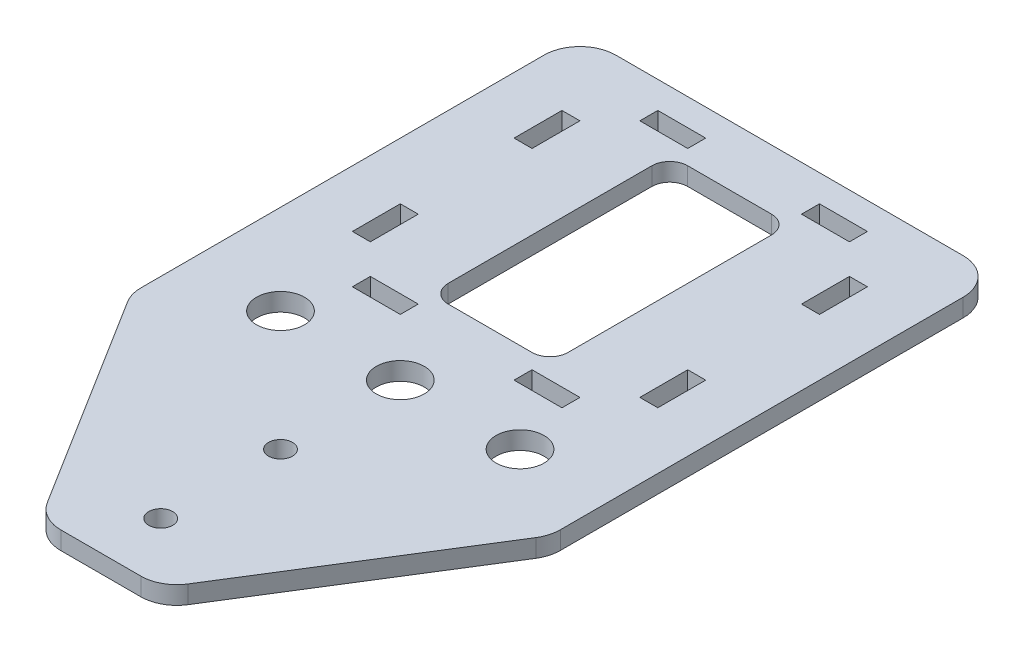
SolidWorks part; units mm, degrees
ref_plane "前视基准面" through (0, 0, 0) normal (0, 0, 1) x (1, 0, 0)
ref_plane "上视基准面" through (0, 0, 0) normal (0, 1, 0) x (1, 0, 0)
ref_plane "右视基准面" through (0, 0, 0) normal (1, 0, 0) x (0, 0, -1)
other "Configuration Table"
sketch "草图1" plane through (0, 0, 0) normal (0, 1, 0) x (1, 0, 0)
  line L0 (-35, -45) -> (-10, -85)
  line L1 (-35, 45) -> (35, 45)
  line L2 (-35, 45) -> (-35, -45)
  line L3 (-35, -45) -> (35, -45)
  line L4 (35, 45) -> (35, -45)
  line L5 (-35, 45) -> (35, -45) construction
  line L6 (-35, -45) -> (35, 45) construction
  line L7 (-10, -45) -> (10, -45)
  line L8 (-10, -45) -> (-10, -85)
  line L9 (-10, -85) -> (10, -85)
  line L10 (10, -45) -> (10, -85)
  line L11 (10, -85) -> (35, -45)
  line L12 (0, -45) -> (0, -55) construction
  line L13 (0, -55) -> (0, -75) construction
  line L14 (-4.6142, 0) -> (3.837, 0) construction
  line L15 (-22.5, 22.5) -> (22.5, 22.5) construction
  line L16 (-22.5, 22.5) -> (-22.5, -22.5) construction
  line L17 (-22.5, -22.5) -> (22.5, -22.5) construction
  line L18 (22.5, 22.5) -> (22.5, -22.5) construction
  line L19 (-22.5, 22.5) -> (22.5, -22.5) construction
  line L20 (-22.5, -22.5) -> (22.5, 22.5) construction
  line L21 (-22.5, 17.5) -> (-25.5, 17.5)
  line L22 (-22.5, 17.5) -> (-22.5, 9.5)
  line L23 (-22.5, 9.5) -> (-25.5, 9.5)
  line L24 (-25.5, 17.5) -> (-25.5, 9.5)
  line L25 (-22.5, -9.5) -> (-25.5, -9.5)
  line L26 (-25.5, -17.5) -> (-25.5, -9.5)
  line L27 (-22.5, -17.5) -> (-25.5, -17.5)
  line L28 (-22.5, -17.5) -> (-22.5, -9.5)
  line L53 (17.5, 22.5) -> (9.5, 22.5)
  line L54 (17.5, 22.5) -> (17.5, 25.5)
  line L55 (17.5, 25.5) -> (9.5, 25.5)
  line L56 (9.5, 22.5) -> (9.5, 25.5)
  line L57 (-9.5, 22.5) -> (-9.5, 25.5)
  line L58 (-17.5, 25.5) -> (-9.5, 25.5)
  line L59 (-17.5, 22.5) -> (-17.5, 25.5)
  line L60 (-17.5, 22.5) -> (-9.5, 22.5)
  line L61 (-17.5, -22.5) -> (-9.5, -22.5)
  line L62 (-17.5, -22.5) -> (-17.5, -25.5)
  line L63 (-17.5, -25.5) -> (-9.5, -25.5)
  line L64 (-9.5, -22.5) -> (-9.5, -25.5)
  line L65 (9.5, -22.5) -> (9.5, -25.5)
  line L66 (17.5, -25.5) -> (9.5, -25.5)
  line L67 (17.5, -22.5) -> (17.5, -25.5)
  line L68 (17.5, -22.5) -> (9.5, -22.5)
  line L69 (22.5, 17.5) -> (25.5, 17.5)
  line L70 (25.5, 17.5) -> (25.5, 9.5)
  line L71 (22.5, 9.5) -> (25.5, 9.5)
  line L72 (22.5, 17.5) -> (22.5, 9.5)
  line L73 (22.5, -17.5) -> (22.5, -9.5)
  line L74 (22.5, -17.5) -> (25.5, -17.5)
  line L75 (25.5, -17.5) -> (25.5, -9.5)
  line L76 (22.5, -9.5) -> (25.5, -9.5)
  circle A0 centre (0, -55) radius 2
  circle A1 centre (0, -75) radius 2
  point P0 (0, 0)
  point P10 (0, -85)
  point P16 (0, 0)
  dimension "D5" = 4
  dimension "D7" = 20
  dimension "D1" = 70
  dimension "D2" = 90
  dimension "D3" = 20
  dimension "D4" = 40
  dimension "D6" = 10
  dimension "D8" = 45
  dimension "D9" = 45
  dimension "D10" = 3
  dimension "D11" = 8
  dimension "D12" = 5
extrude "凸台-拉伸1" add sketch "草图1" along normal blind 3 contours L4 L1 L2 L3 | L8 L3 L0 | L10 L3 L8 L9 A1 A0 | L10 L11 L3
sketch "草图2" plane through (0, 3, 0) normal (0, 1, 0) x (1, 0, 0)
  line L0 (0, -55) -> (0, -35) construction
  line L1 (0, -35) -> (-20, -35) construction
  circle A0 centre (0, -35) radius 4
  circle A1 centre (-20, -35) radius 4
  circle A2 centre (20, -35) radius 4
  dimension "D2" = 8
  dimension "D3" = 20
  dimension "D1" = 20
extrude "切除-拉伸1" cut sketch "草图2" against normal blind 10
sketch "草图3" plane through (0, 3, 0) normal (0, 1, 0) x (1, 0, 0)
  line L0 (35, 45) -> (35, -45) construction
  line L1 (-35, 45) -> (35, 45)
  line L2 (-35, 45) -> (-35, 30)
  line L3 (-35, 30) -> (35, 30)
  line L4 (35, 45) -> (35, 30)
  dimension "D1" = 15
extrude "切除-拉伸2" cut sketch "草图3" against normal blind 10
sketch "草图4" plane through (0, 3, 0) normal (0, 1, 0) x (1, 0, 0)
  line L1 (-10, 20) -> (10, 20)
  line L2 (-10, 20) -> (-10, -20)
  line L3 (-10, -20) -> (10, -20)
  line L4 (10, 20) -> (10, -20)
  line L5 (-10, 20) -> (10, -20) construction
  line L6 (-10, -20) -> (10, 20) construction
  point P0 (0, 0)
  dimension "D1" = 20
  dimension "D2" = 40
extrude "切除-拉伸3" cut sketch "草图4" against normal blind 10
fillet "圆角1" radius 3 4 edges at (-10, 1.5, 20) (10, 1.5, 20) (10, 1.5, -20) (-10, 1.5, -20)
fillet "圆角2" radius 6 6 edges at (-35, 1.5, 45) (35, 1.5, 45) (-10, 1.5, 85) (10, 1.5, 85) (35, 1.5, -30) (-35, 1.5, -30)
